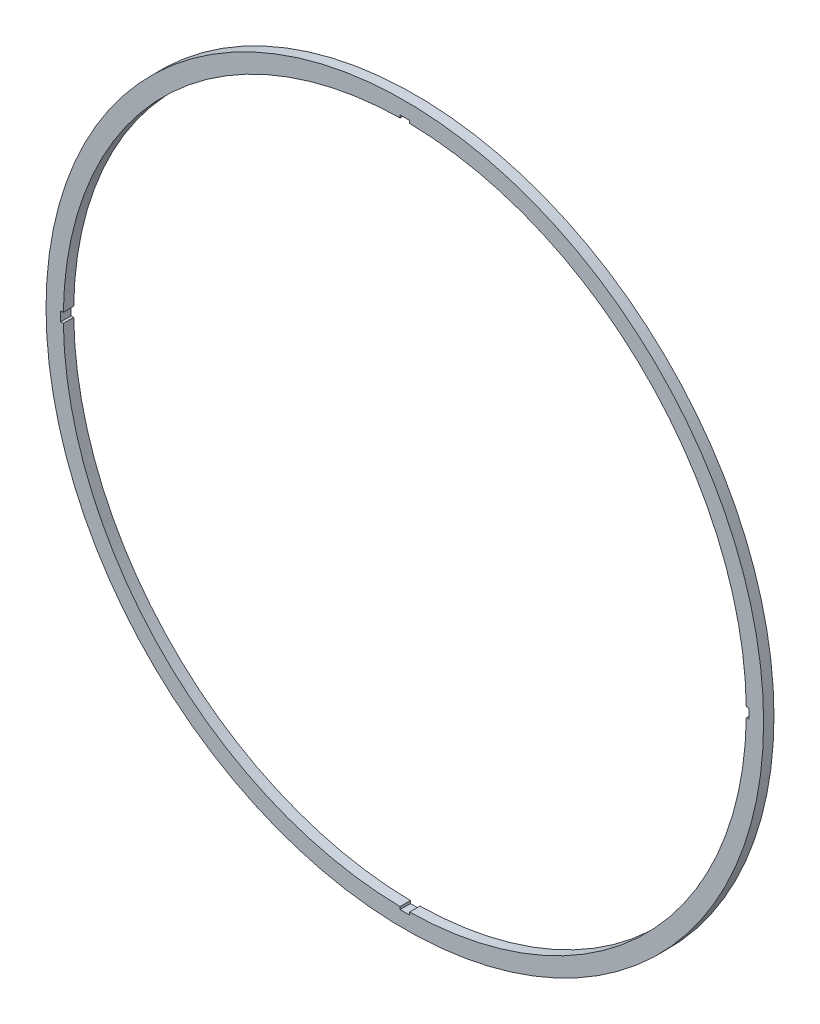
SolidWorks part; units mm, degrees
ref_plane "Front Plane" through (0, 0, 0) normal (0, 0, 1) x (1, 0, 0)
ref_plane "Top Plane" through (0, 0, 0) normal (0, 1, 0) x (1, 0, 0)
ref_plane "Right Plane" through (0, 0, 0) normal (1, 0, 0) x (0, 0, -1)
sketch "Sketch1" plane through (0, 0, 0) normal (0, 0, 1) x (1, 0, 0)
  line L0 (0, 0) -> (0, 484.7894) construction
  line L1 (398.0034, 5.5116) -> (394.9615, 5.5116)
  line L2 (-5.5116, 398.0034) -> (5.5116, 398.0034)
  line L3 (-5.5116, 398.0034) -> (-5.5116, 394.9615)
  line L5 (5.5116, 398.0034) -> (5.5116, 394.9615)
  line L6 (-5.5116, 398.0034) -> (0, 395) construction
  line L7 (0, 395) -> (5.5116, 398.0034) construction
  line L8 (398.0034, 5.5116) -> (398.0034, -5.5116)
  line L9 (398.0034, -5.5116) -> (394.9615, -5.5116)
  line L10 (5.5116, -398.0034) -> (5.5116, -394.9615)
  line L11 (5.5116, -398.0034) -> (-5.5116, -398.0034)
  line L12 (-5.5116, -398.0034) -> (-5.5116, -394.9615)
  line L13 (-398.0034, -5.5116) -> (-394.9615, -5.5116)
  line L14 (-398.0034, -5.5116) -> (-398.0034, 5.5116)
  line L15 (-398.0034, 5.5116) -> (-394.9615, 5.5116)
  circle A0 centre (0, 0) radius 415
  arc A1 (-5.5116, 394.9615) -> (-394.9615, 5.5116) centre (0, 0) ccw
  arc A2 (394.9615, 5.5116) -> (5.5116, 394.9615) centre (0, 0) ccw
  circle A3 centre (0, 0) radius 395 construction
  arc A4 (5.5116, -394.9615) -> (394.9615, -5.5116) centre (0, 0) ccw
  arc A5 (-394.9615, -5.5116) -> (-5.5116, -394.9615) centre (0, 0) ccw
  point P5 (0, 395)
  point P7 (430, 0)
  dimension "D1" = 20
  dimension "D3" = 830
  dimension "D2" = 4
extrude "Boss-Extrude1" add sketch "Sketch1" along normal blind 12
